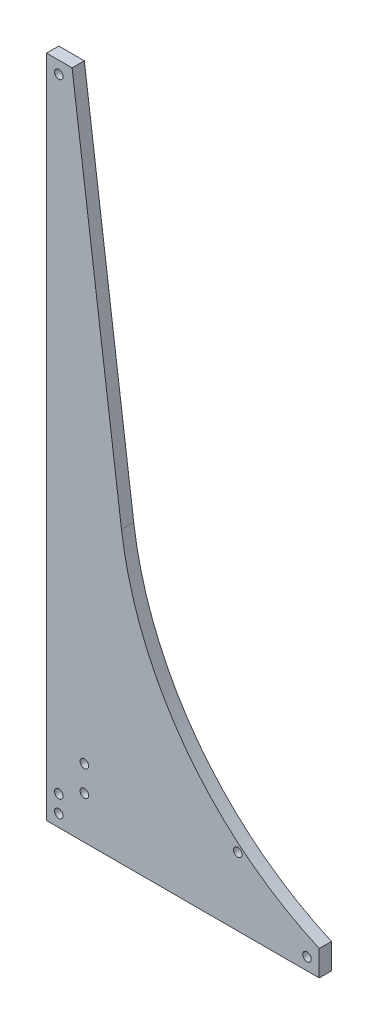
SolidWorks part; units mm, degrees
material "Pine"
ref_plane "Front Plane" through (0, 0, 0) normal (0, 0, 1) x (1, 0, 0)
ref_plane "Top Plane" through (0, 0, 0) normal (0, 1, 0) x (1, 0, 0)
ref_plane "Right Plane" through (0, 0, 0) normal (1, 0, 0) x (0, 0, -1)
sketch "Sketch1" plane through (0, 0, 0) normal (0, 0, 1) x (1, 0, 0)
  line L0 (0, 0) -> (406.4, 0)
  line L1 (0, 0) -> (0, 990.6)
  line L3 (0, 990.6) -> (38.1, 990.6)
  line L4 (38.1, 990.6) -> (111.6674, 431.8)
  line L6 (406.4, 38.1) -> (406.4, 0)
  circle A1 centre (18.2562, 18.2562) radius 6.35
  circle A2 centre (388.1438, 18.2562) radius 6.35
  circle A3 centre (18.2562, 972.3438) radius 6.35
  circle A4 centre (56.3562, 101.6) radius 6.35
  circle A5 centre (284.9562, 101.6) radius 6.35
  circle A6 centre (18.2562, 43.6562) radius 6.35
  circle A7 centre (56.3562, 63.5) radius 6.35
  arc A8 (111.6674, 431.8) -> (406.4, 38.1) centre (609.539, 497.346) ccw
  dimension "D7" = 12.7
  dimension "D8" = 18.2562
  dimension "D10" = 18.2562
  dimension "D12" = 18.2562
  dimension "D14" = 12.7
  dimension "D15" = 25.4
  dimension "D16" = 18.2562
  dimension "D17" = 101.6
  dimension "D18" = 101.6
  dimension "D19" = 228.6
  dimension "D22" = 228.6
  dimension "D24" = 12.7
  dimension "D1" = 406.4
  dimension "D2" = 990.6
  dimension "D3" = 38.1
  dimension "D4" = 38.1
  dimension "D5" = 558.8
  dimension "D6" = 97.5
  dimension "D9" = 18.2562
  dimension "D13" = 18.2562
  dimension "D20" = 38.1
  dimension "D21" = 38.1
extrude "Boss-Extrude1" add sketch "Sketch1" along normal blind 18.2562
